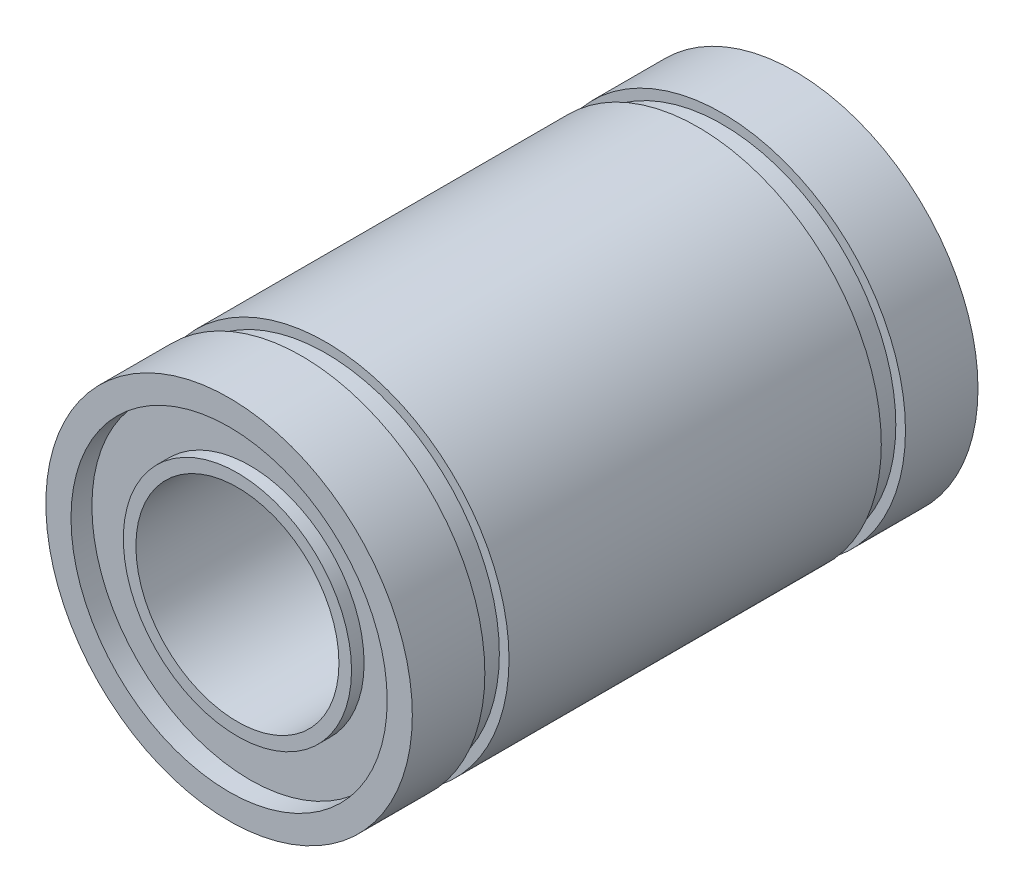
SolidWorks part; units mm, degrees
ref_plane "Front Plane" through (0, 0, 0) normal (0, 0, 1) x (1, 0, 0)
ref_plane "Top Plane" through (0, 0, 0) normal (0, 1, 0) x (1, 0, 0)
ref_plane "Right Plane" through (0, 0, 0) normal (1, 0, 0) x (0, 0, -1)
sketch "Sketch1" plane through (0, 0, 0) normal (0, 0, 1) x (1, 0, 0)
  circle A0 centre (0, 0) radius 9.475
  dimension "D1" = 18.95
extrude "Boss-Extrude1" add sketch "Sketch1" along normal blind 29.25
sketch "Sketch2" plane through (0, 0, 0) normal (0, 1, 0) x (1, 0, 0)
  line L0 (9.475, -29.25) -> (9.475, 0) construction
  line L1 (9.475, -3.75) -> (8.975, -3.75)
  line L2 (9.475, -3.75) -> (9.475, -5)
  line L3 (9.475, -5) -> (8.975, -5)
  line L4 (8.975, -3.75) -> (8.975, -5)
  line L5 (9.475, 0) -> (-9.475, 0) construction
  line L6 (9.475, -24.25) -> (8.975, -24.25)
  line L7 (9.475, -24.25) -> (9.475, -25.5)
  line L8 (9.475, -25.5) -> (8.975, -25.5)
  line L9 (8.975, -24.25) -> (8.975, -25.5)
  line L10 (-9.475, -29.25) -> (9.475, -29.25) construction
  dimension "D1" = 3.75
  dimension "D2" = 3.75
  dimension "D3" = 1.25
  dimension "D4" = 1.25
  dimension "D5" = 0.5
  dimension "D6" = 0.5
ref_axis "Axis1" through (0, 0, 29.25) along (0, 0, -1)
sketch "Sketch4" plane through (0, 0, 0) normal (0, 1, 0) x (1, 0, 0)
  line L0 (0, -29.2691) -> (0, 0)
  line L1 (0, -29.25) -> (0, 0) construction
  point P5 (0, -14.6345)
  dimension "D1" = 29.2691
revolve "Cut-Revolve1" cut sketch "Sketch2" angle 360 about axis through (0, 0, 29.25) along (0, 0, -1)
sketch "Sketch3" plane through (0, 0, 0) normal (0, 1, 0) x (1, 0, 0)
  line L5 (0, -29.25) -> (0, 0) construction
  line L6 (8.175, 0) -> (0, 0)
  line L7 (8.175, 0) -> (8.175, -1.1)
  line L8 (8.175, -1.1) -> (0, -1.1)
  line L9 (0, 0) -> (0, -1.1)
  dimension "D1" = 1.1
  dimension "D2" = 1.1
  dimension "D3" = 8.175
revolve "Cut-Revolve2" cut sketch "Sketch3" angle 360 about axis through (0, 0, 29.25) along (0, 0, -1)
ref_plane "Plane1" through (0, 0, 14.6345) normal (0, 0, 1) x (1, 0, 0)
mirror "Mirror1" about plane through (0, 0, 14.6345) normal (0, 0, 1) of "Cut-Revolve2"
ref_point "Point1"
hole_wizard "Ø10.5 (10.5) Diameter Hole1" positions "Sketch8" profile "Sketch9" hole size "Ø10.5" standard "ANSI Metric" end condition through all
sketch "Sketch8" plane through (0, 0, 1.1) normal (0, 0, -1) x (-1, 0, 0)
  point P0 (0, 0)
sketch "Sketch9" plane through (0, 0, 1.1) normal (1, 0, 0) x (0, 1, 0)
  line L0 (0, 0) -> (0, 28.15)
  line L1 (0, 28.15) -> (5.25, 28.15)
  line L2 (5.25, 28.15) -> (5.25, 0)
  line L5 (5.25, 0) -> (0, 0)
  line L11 (0, -6.35) -> (0, 107.95) construction
  dimension "Thru Hole Dia." = 10.5
  dimension "Thru Hole Depth" = 28.15
sketch "Sketch10" plane through (0, 0, 0) normal (1, 0, 0) x (0, 0, -1)
  line L0 (-1.1, -8.175) -> (-1.1, 8.175) construction
  line L1 (-1.1, 5.25) -> (-0.45, 5.25)
  line L2 (-1.1, 5.25) -> (-1.1, 5.9)
  line L3 (-1.1, 5.9) -> (-0.45, 5.9)
  line L4 (-0.45, 5.25) -> (-0.45, 5.9)
  line L5 (-1.1, -5.25) -> (-1.1, 5.25) construction
  line L6 (-29.2691, 0) -> (0, 0) construction
  dimension "D1" = 5.25
  dimension "D2" = 0.65
  dimension "D3" = 0.65
revolve "Revolve1" add sketch "Sketch10" angle 360 about L0
mirror "Mirror2" about plane through (0, 0, 14.6345) normal (0, 0, 1) of "Revolve1"
